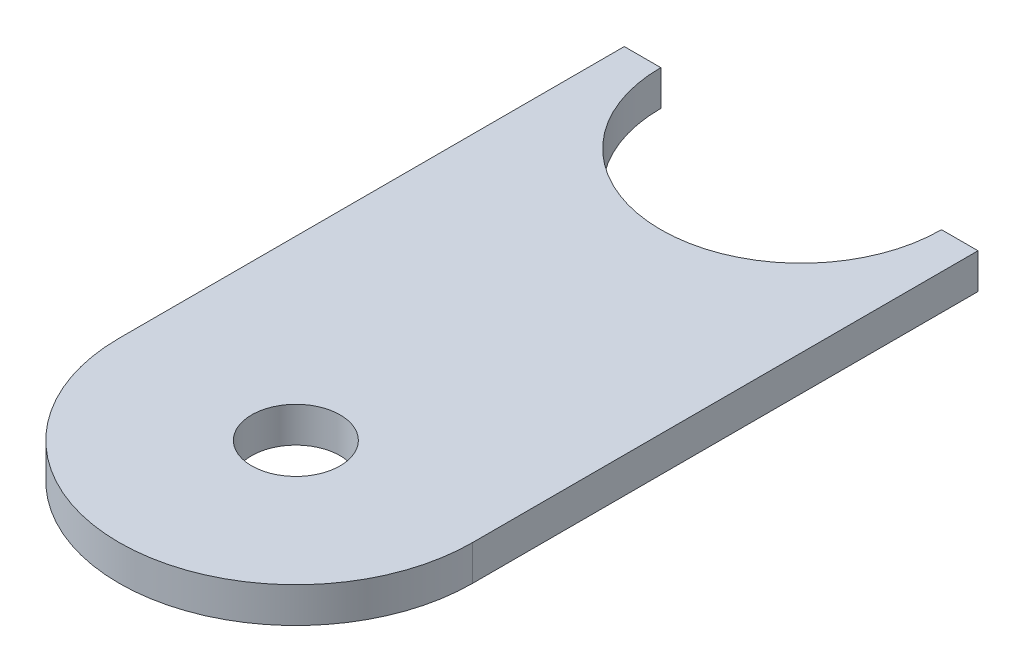
SolidWorks part; units mm, degrees
ref_plane "Front Plane" through (0, 0, 0) normal (0, 0, 1) x (1, 0, 0)
ref_plane "Top Plane" through (0, 0, 0) normal (0, 1, 0) x (1, 0, 0)
ref_plane "Right Plane" through (0, 0, 0) normal (1, 0, 0) x (0, 0, -1)
sketch "Sketch1" plane through (0, 0, 0) normal (0, 1, 0) x (1, 0, 0)
  line L0 (-20, 0) -> (20, 0) construction
  line L1 (20, 0) -> (20, -57.1429)
  line L2 (-20, -57.1429) -> (-20, 0)
  line L3 (20, 0) -> (15.875, 0)
  line L4 (-20, 0) -> (-15.875, 0)
  arc A0 (20, -57.1429) -> (-20, -57.1429) centre (0, -57.1429) cw
  circle A1 centre (0, -57.1429) radius 5
  arc A2 (15.875, 0) -> (-15.875, 0) centre (0, 0) cw
  dimension "D3" = 10
  dimension "D5" = 15.875
  dimension "D1" = 40
  dimension "D2" = 57.1429
extrude "Boss-Extrude1" add sketch "Sketch1" along normal blind 4
equation "\"D2@Sketch1\"=\"D1@Sketch1\"/0.7"
